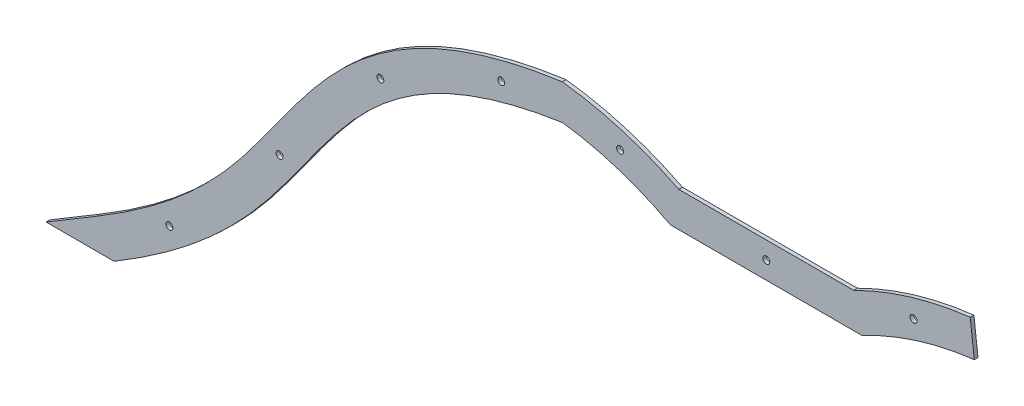
SolidWorks part; units mm, degrees
ref_plane "前视基准面" through (0, 0, 0) normal (0, 0, 1) x (1, 0, 0)
ref_plane "上视基准面" through (0, 0, 0) normal (0, 1, 0) x (1, 0, 0)
ref_plane "右视基准面" through (0, 0, 0) normal (1, 0, 0) x (0, 0, -1)
sketch "Sketch1" plane through (0, 0, 0) normal (0, 0, 1) x (1, 0, 0)
  line L0 (25, 170) -> (175, 170)
  line L1 (17.6763, 140) -> (182.3237, 140)
  line L2 (-475, -100) -> (-518.0311, -125.7444)
  line L3 (-518.0311, -125.7444) -> (-459.5978, -125.7444)
  line L4 (278.4889, 170.2036) -> (275, 200)
  line L5 (-467.2989, -112.8722) -> (-510.33, -138.6166) construction
  line L6 (21.3892, 155) -> (178.6108, 155) construction
  arc A0 (-75, 200) -> (25, 170) centre (-109.8893, -97.9643) cw
  arc A1 (175, 170) -> (275, 200) centre (309.8893, -97.9643) cw
  arc A2 (-74.6961, 169.7322) -> (17.6763, 140) centre (-109.8893, -97.9643) cw
  arc A3 (182.3237, 140) -> (278.4889, 170.2036) centre (309.8893, -97.9643) cw
  arc A4 (-74.8355, 184.8717) -> (21.3892, 155) centre (-109.8893, -97.9643) cw construction
  arc A5 (178.6108, 155) -> (276.7445, 185.1018) centre (309.8893, -97.9643) cw construction
  circle A6 centre (-412.1745, -75.7444) radius 3
  circle A7 centre (-317.6018, 24.2556) radius 3
  circle A8 centre (-231.0967, 124.2556) radius 3
  circle A9 centre (-127.4115, 174.2556) radius 3
  circle A10 centre (100, 155) radius 3
  circle A11 centre (226.3113, 174.5053) radius 3
  circle A12 centre (-25.3926, 174.2218) radius 3
  spline S0 degree 3 poles (-475, -100) (-419.5406, -66.8201) (-306.0139, 34.0368) (-257.6356, 174.2871) (-75, 200) knots 0 0 0 0 0.312224 1 1 1 1
  spline S1 degree 1 poles (-459.5978, -125.7444) (-74.6961, 169.7322) knots 0 0 1 1 construction
  spline S2 degree 3 poles (-459.5978, -125.7444) (-458.1678, -124.8889) (-455.301, -123.1604) (-449.693, -119.7258) (-442.8445, -115.4302) (-434.8975, -110.2806) (-424.643, -103.4106) (-412.4462, -94.8074) (-398.7329, -84.4255) (-385.8755, -73.9567) (-369.7872, -59.85) (-355.1526, -45.4768) (-341.7181, -30.7847) (-332.1609, -19.5812) (-323.1016, -8.241) (-311.6308, 6.8636) (-298.1175, 25.606) (-282.3957, 47.4316) (-266.3843, 68.251) (-249.3412, 87.8034) (-230.505, 105.9281) (-212.6012, 119.774) (-196.4574, 130.0489) (-183.3039, 137.3321) (-168.9692, 144.1624) (-153.318, 150.5001) (-136.2188, 156.2966) (-120.6588, 160.6298) (-107.3641, 163.768) (-96.9585, 165.9492) (-87.9034, 167.6182) (-80.4453, 168.8567) (-76.6048, 169.4489) (-74.6961, 169.7322) knots 0 0 0 0 0.007772 0.015544 0.031088 0.046632 0.062176 0.093264 0.124353 0.155441 0.186529 0.248705 0.279793 0.310882 0.34197 0.373058 0.435234 0.497411 0.559587 0.621763 0.68394 0.746116 0.777204 0.808292 0.83938 0.870469 0.901557 0.932645 0.948189 0.963733 0.979277 0.987049 0.994821 0.994821 0.994821 0.994821
  spline S3 degree 1 poles (-467.2989, -112.8722) (-74.8355, 184.8717) knots 0 0 1 1 construction
  spline S4 degree 3 poles (-467.2989, -112.8722) (-465.8947, -112.0321) (-463.0786, -110.3342) (-457.5762, -106.964) (-450.8636, -102.7531) (-443.0868, -97.7125) (-433.0675, -90.9979) (-423.8922, -84.5226) (-415.1487, -78.0342) (-409.9698, -74.0603) (-403.2446, -68.7575) (-394.6932, -61.7429) (-379.8313, -48.6964) (-362.184, -31.3406) (-343.2714, -9.8317) (-330.2359, 7.0702) (-320.4577, 20.3068) (-314.9027, 27.9731) (-305.7278, 40.7071) (-293.9593, 57.0194) (-277.6315, 78.2128) (-259.7555, 98.6534) (-244.7781, 112.9919) (-233.8839, 122.0718) (-226.3196, 128.0284) (-216.2598, 135.2631) (-203.2116, 143.4936) (-189.1356, 151.2095) (-173.8464, 158.4123) (-157.2257, 165.0566) (-142.3522, 170.0254) (-131.3386, 173.2066) (-124.74, 174.9742) (-117.7908, 176.7319) (-108.8769, 178.7966) (-98.0064, 181.0287) (-88.5695, 182.7287) (-80.809, 183.9859) (-76.8191, 184.5852) (-74.8355, 184.8717) knots 0 0 0 0 0.007793 0.015586 0.031172 0.046758 0.062344 0.093516 0.106904 0.12249 0.130283 0.155861 0.187033 0.249377 0.311721 0.374065 0.391607 0.422779 0.438365 0.498754 0.561098 0.623442 0.685786 0.700893 0.71648 0.748131 0.779303 0.810475 0.841647 0.872819 0.903991 0.918626 0.926419 0.935163 0.950749 0.966335 0.981921 0.989714 0.997507 0.997507 0.997507 0.997507 construction
  dimension "D5" = 300
  dimension "D8" = 300
  dimension "D14" = 50
  dimension "D18" = 6
  dimension "D19" = 6
  dimension "D20" = 6
  dimension "D21" = 6
  dimension "D22" = 6
  dimension "D23" = 6
  dimension "D24" = 6
  dimension "D1" = 120
  dimension "D2" = 100
  dimension "D3" = 400
  dimension "D4" = 300
  dimension "D6" = 100
  dimension "D7" = 30
  dimension "D9" = 100
  dimension "D10" = 30
  dimension "D11" = 150
  dimension "D13" = 15
  dimension "D15" = 150
  dimension "D16" = 250
  dimension "D17" = 300
  dimension "D12" = 30
extrude "Boss-Extrude1" add sketch "Sketch1" along normal blind 3.175
